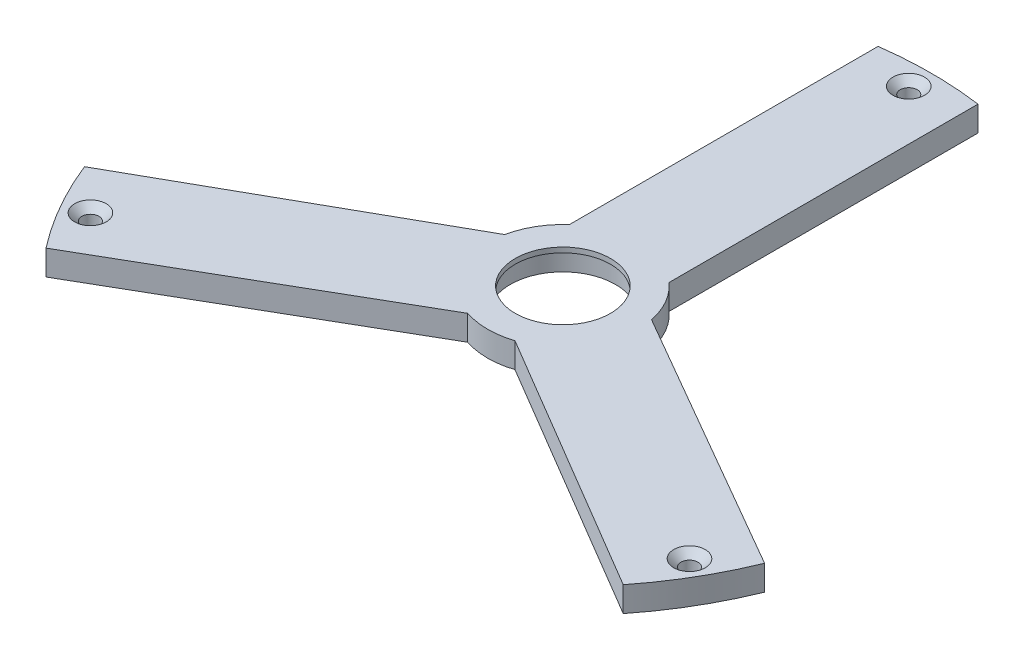
SolidWorks part; units mm, degrees
ref_plane "Alzado" through (0, 0, 0) normal (0, 0, 1) x (1, 0, 0)
ref_plane "Planta" through (0, 0, 0) normal (0, 1, 0) x (1, 0, 0)
ref_plane "Vista lateral" through (0, 0, 0) normal (1, 0, 0) x (0, 0, -1)
sketch "Croquis1" plane through (0, 0, 0) normal (0, 1, 0) x (1, 0, 0)
  line L0 (-9.9443, 11.2299) -> (-9.9443, 72.8242)
  line L5 (10, 10) -> (-12.7983, -12.7983) construction
  line L6 (10, -10) -> (0, 0) construction
  line L7 (10, 11.1803) -> (10, 72.8166)
  line L12 (-9.9443, 9.9443) -> (-10, 10) construction
  line L13 (14.6975, 2.9971) -> (68.0397, -27.8001)
  line L14 (4.6894, -14.2481) -> (57.6435, -45.6013)
  line L15 (-4.7532, -14.227) -> (-58.0954, -45.0241)
  line L16 (-14.6838, 3.0636) -> (-68.3136, -27.12)
  line L17 (-6.0466, 8.056) -> (-7.3205, 7.3205) [skipped]
  line L18 (-3.9534, -9.2645) -> (-2.6795, -10) [skipped]
  arc A7 (10, 72.8166) -> (-9.9443, 72.8242) centre (0, 0) ccw
  arc A8 (-68.3136, -27.12) -> (-58.0954, -45.0241) centre (0, 0) ccw
  arc A9 (57.6435, -45.6013) -> (68.0397, -27.8001) centre (0, 0) ccw
  arc A10 (14.6975, 2.9971) -> (10, 11.1803) centre (0, 0) ccw
  arc A11 (-4.7532, -14.227) -> (4.6894, -14.2481) centre (0, 0) ccw
  arc A12 (-9.9443, 11.2299) -> (-14.6838, 3.0636) centre (0, 0) ccw
  point P0 (0, 0)
  point P27 (0, 0)
  dimension "D3" = 147
  dimension "D4" = 30
  dimension "D1" = 20
  dimension "D2" = 20
  dimension "D5" = 3
extrude "Saliente-Extruir1" add sketch "Croquis1" along normal blind 5
sketch "Croquis6" plane through (0, 5, 0) normal (0, 1, 0) x (1, 0, 0)
  circle A0 centre (0, 69) radius 1.6
  circle A1 centre (59.7558, -34.5) radius 1.6
  circle A2 centre (-59.7558, -34.5) radius 1.6
  point P10 (0, 0)
  dimension "D1" = 3.2
  dimension "D2" = 69
  dimension "D3" = 3
extrude "Cortar-Extruir4" cut sketch "Croquis6" along normal mid plane 20
sketch "Croquis8" plane through (0, 0, 0) normal (0, -1, 0) x (1, 0, 0)
  circle A0 centre (0, 0) radius 10.5
  dimension "D1" = 21
extrude "Cortar-Extruir5" cut sketch "Croquis8" against normal blind 4
sketch "Croquis9" plane through (0, 5, 0) normal (0, 1, 0) x (1, 0, 0)
  circle A0 centre (0, 0) radius 9.5
  dimension "D1" = 19
extrude "Cortar-Extruir6" cut sketch "Croquis9" against normal blind 4
hole_wizard "CSK for M3 Flat Head Machine Screw1" positions "Sketch1" profile "Sketch2" countersink size "M3" standard "ANSI Metric" end condition through all
sketch "Sketch1" plane through (0, 5, 0) normal (0, 1, 0) x (1, 0, 0)
  point P0 (-59.7558, -34.5)
  point P3 (0, 69)
  point P6 (59.7558, -34.5)
sketch "Sketch2" plane through (-59.7558, 5, 34.5) normal (1, 0, 0) x (0, 0, 1)
  line L0 (0, 0) -> (0, 5)
  line L1 (0, 5) -> (1.7, 5)
  line L2 (1.7, 5) -> (1.7, 1.45)
  line L3 (1.7, 1.45) -> (3.15, 0)
  line L5 (3.15, 0) -> (0, 0)
  line L6 (-1.7, 1.45) -> (-3.15, 0) construction
  line L11 (0, -6.35) -> (0, 107.95) construction
  dimension "Thru Hole Dia." = 3.4
  dimension "Thru Hole Depth" = 5
  dimension "Near C'Sink Dia." = 6.3
  dimension "Near C'Sink Angle" = 90
